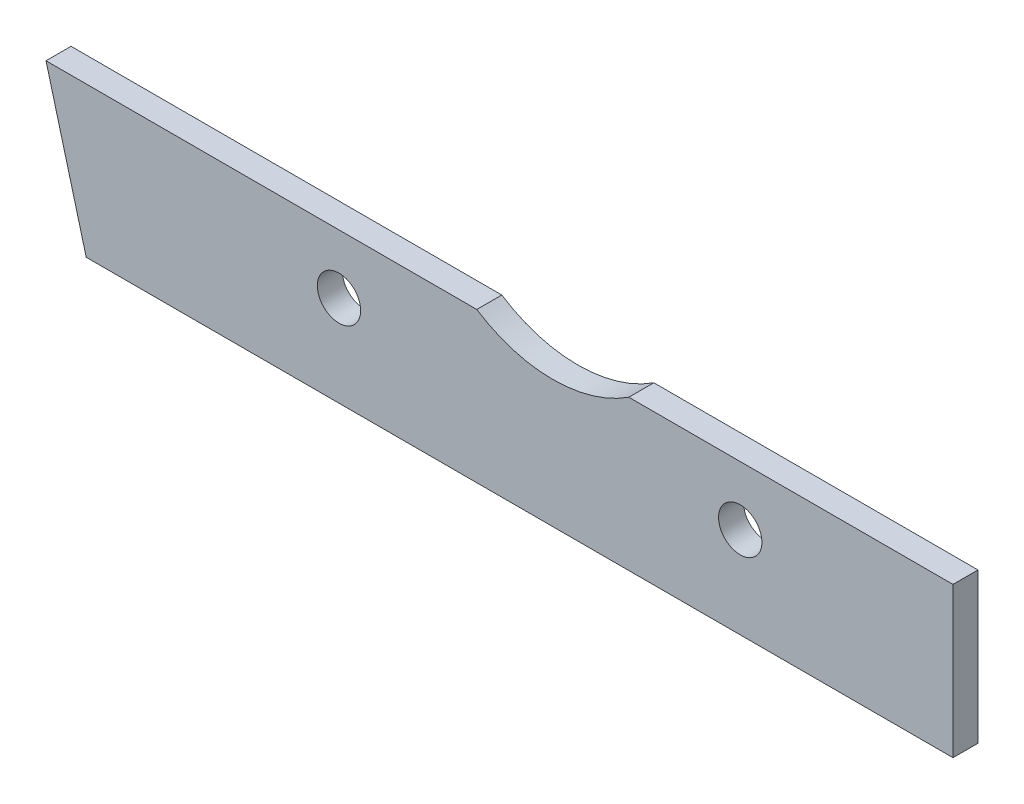
SolidWorks part; units mm, degrees
material "Plain Carbon Steel"
ref_plane "Front Plane" through (0, 0, 0) normal (0, 0, 1) x (1, 0, 0)
ref_plane "Top Plane" through (0, 0, 0) normal (0, 1, 0) x (1, 0, 0)
ref_plane "Right Plane" through (0, 0, 0) normal (1, 0, 0) x (0, 0, -1)
sketch "Sketch1" plane through (0, 0, 0) normal (0, 0, 1) x (1, 0, 0)
  line L1 (-94.8285, -355.15) -> (-204.8285, -355.15)
  line L2 (-94.8285, -355.15) -> (-94.8285, -336.1)
  line L3 (-94.8285, -336.1) -> (-135.9694, -336.1)
  line L4 (-204.8285, -355.15) -> (-209.9329, -336.1)
  line L6 (-155.261, -336.1) -> (-209.9329, -336.1)
  circle A0 centre (-121.8285, -343.6) radius 2.75
  circle A1 centre (-172.7484, -343.6) radius 2.75
  arc A2 (-135.9694, -336.1) -> (-155.261, -336.1) centre (-145.6152, -321.3355) cw
  dimension "D3" = 5.5
  dimension "D1" = 75
  dimension "D2" = 19.05
  dimension "D4" = 50.92
  dimension "D5" = 27
  dimension "D6" = 7.5
  dimension "D7" = 110
extrude "Boss-Extrude1" add sketch "Sketch1" against normal blind 3.175
